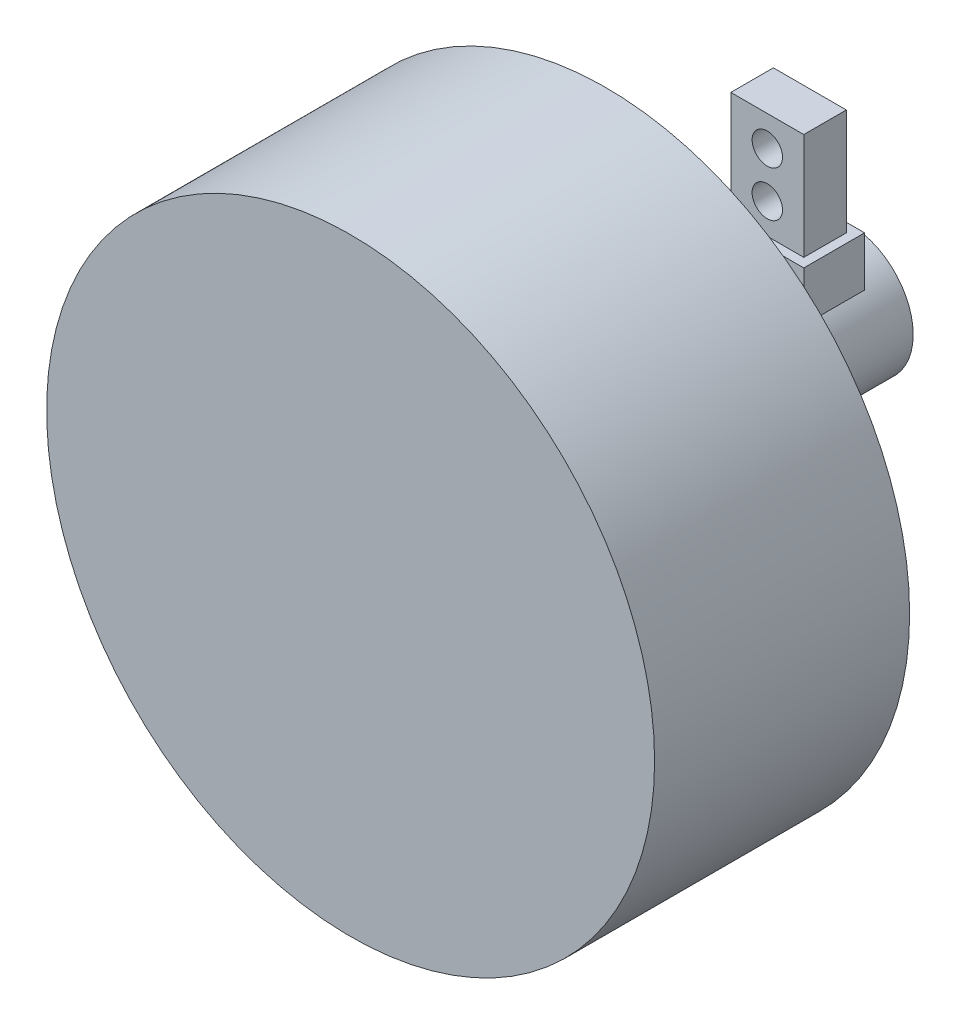
SolidWorks part; units mm, degrees
ref_plane "Front Plane" through (0, 0, 0) normal (0, 0, 1) x (1, 0, 0)
ref_plane "Top Plane" through (0, 0, 0) normal (0, 1, 0) x (1, 0, 0)
ref_plane "Right Plane" through (0, 0, 0) normal (1, 0, 0) x (0, 0, -1)
sketch "Sketch1" plane through (0, 0, 0) normal (0, 0, 1) x (1, 0, 0)
  circle A0 centre (0, 0) radius 100
  dimension "D1" = 200
extrude "Body" add sketch "Sketch1" along normal blind 83.89
sketch "Sketch2" plane through (0, 0, 0) normal (0, 0, 1) x (1, 0, 0)
  circle A0 centre (0, 0) radius 20.985
  dimension "D1" = 41.97
extrude "Shaft" add sketch "Sketch2" against normal blind 80.18
ref_plane "Tangent Plane" through (0, 20.985, 0) normal (0, 1, 0) x (1, 0, 0)
sketch "Sketch5" plane through (0, 20.985, 0) normal (0, 1, 0) x (1, 0, 0)
  line L0 (0, 0) -> (0, 80.18) construction
  line L1 (20.985, 80.18) -> (-20.985, 80.18) construction
  line L3 (15, 50.18) -> (-15, 50.18)
  line L4 (15, 50.18) -> (15, 70.18)
  line L5 (15, 70.18) -> (-15, 70.18)
  line L6 (-15, 50.18) -> (-15, 70.18)
  line L7 (15, 50.18) -> (-15, 70.18) construction
  line L8 (15, 70.18) -> (-15, 50.18) construction
  point P5 (0, 60.18)
  dimension "D2" = 30
  dimension "D3" = 10
extrude "Mount Base" add sketch "Sketch5" along normal blind 45 and the other way up to surface
sketch "Sketch6" plane through (0, 65.985, 0) normal (0, 1, 0) x (1, 0, 0)
  line L1 (-15, 70.18) -> (15, 70.18)
  line L2 (-15, 70.18) -> (-15, 50.18)
  line L3 (-15, 50.18) -> (15, 50.18)
  line L4 (15, 70.18) -> (15, 50.18)
  line L5 (12, 53.18) -> (-12, 53.18)
  line L6 (12, 53.18) -> (12, 67.18)
  line L7 (12, 67.18) -> (-12, 67.18)
  line L8 (-12, 53.18) -> (-12, 67.18)
  line L9 (12, 53.18) -> (-12, 67.18) construction
  line L10 (12, 67.18) -> (-12, 53.18) construction
  point P6 (0, 60.18)
  dimension "D1" = 3
  dimension "D2" = 3
  dimension "D3" = 3
  dimension "D4" = 3
extrude "Mount Tongue" cut sketch "Sketch6" against normal blind 35
sketch "Sketch7" plane through (0, 0, -67.18) normal (0, 0, -1) x (-1, 0, 0)
  line L0 (0, 30.985) -> (0, 65.985) construction
  line L1 (-15, 30.985) -> (15, 30.985) construction
  line L2 (-12, 65.985) -> (12, 65.985) construction
  circle A0 centre (0, 40.985) radius 5
  circle A1 centre (0, 55.985) radius 5
  dimension "D3" = 10
  dimension "D1" = 10
  dimension "D2" = 10
  dimension "D4" = 10
extrude "Mount Holes" cut sketch "Sketch7" against normal up to next
equation "\"middle_wheel_shaft_diameter\"= 41.97mm"
equation "\"middle_wheel_shaft_length\"= 80.18mm"
equation "\"middle_wheel_shaft_overhang\"= 10.0mm"
equation "\"wheel_diameter\"= 200.0mm"
equation "\"wheel_thickness\"= 83.89mm"
equation "\"linkage_mount_tongue_length\"= 35.0mm"
equation "\"linkage_mount_shoulder_depth\"= 3.0mm"
equation "\"linkage_mount_bolt_diameter\"= 10.0mm"
equation "\"linkage_mount_bolt_spacing\"= 5.0mm"
equation "\"D1@Sketch1\"=\"wheel_diameter\""
equation "\"D1@Body\" = \"wheel_thickness\""
equation "\"D1@Sketch2\"=\"middle_wheel_shaft_diameter\""
equation "\"D1@Shaft\"=\"middle_wheel_shaft_length\""
equation "\"linkage_thickness\"= 20.0mm"
equation "\"linkage_width\"= 30.0mm"
equation "\"linkage_mount_base_length\"= 10.0mm"
equation "\"D1@Sketch5\"=\"linkage_thickness\""
equation "\"D2@Sketch5\"=\"linkage_width\""
equation "\"D3@Sketch5\"=\"middle_wheel_shaft_overhang\""
equation "\"D1@Mount Base\" = \"linkage_mount_base_length\" + \"linkage_mount_tongue_length\""
equation "\"D2@Sketch6\"=\"linkage_mount_shoulder_depth\""
equation "\"D1@Sketch6\"=\"linkage_mount_shoulder_depth\""
equation "\"D3@Sketch6\"=\"linkage_mount_shoulder_depth\""
equation "\"D4@Sketch6\"=\"linkage_mount_shoulder_depth\""
equation "\"D1@Mount Tongue\"=\"linkage_mount_tongue_length\""
equation "\"D1@Sketch7\"=\"linkage_mount_bolt_diameter\""
equation "\"D2@Sketch7\"=\"linkage_mount_bolt_diameter\""
equation "\"D3@Sketch7\"=\"linkage_mount_bolt_spacing\"+\"linkage_mount_bolt_diameter\"/2"
equation "\"D4@Sketch7\"=\"linkage_mount_bolt_spacing\"+\"linkage_mount_bolt_diameter\"/2"
